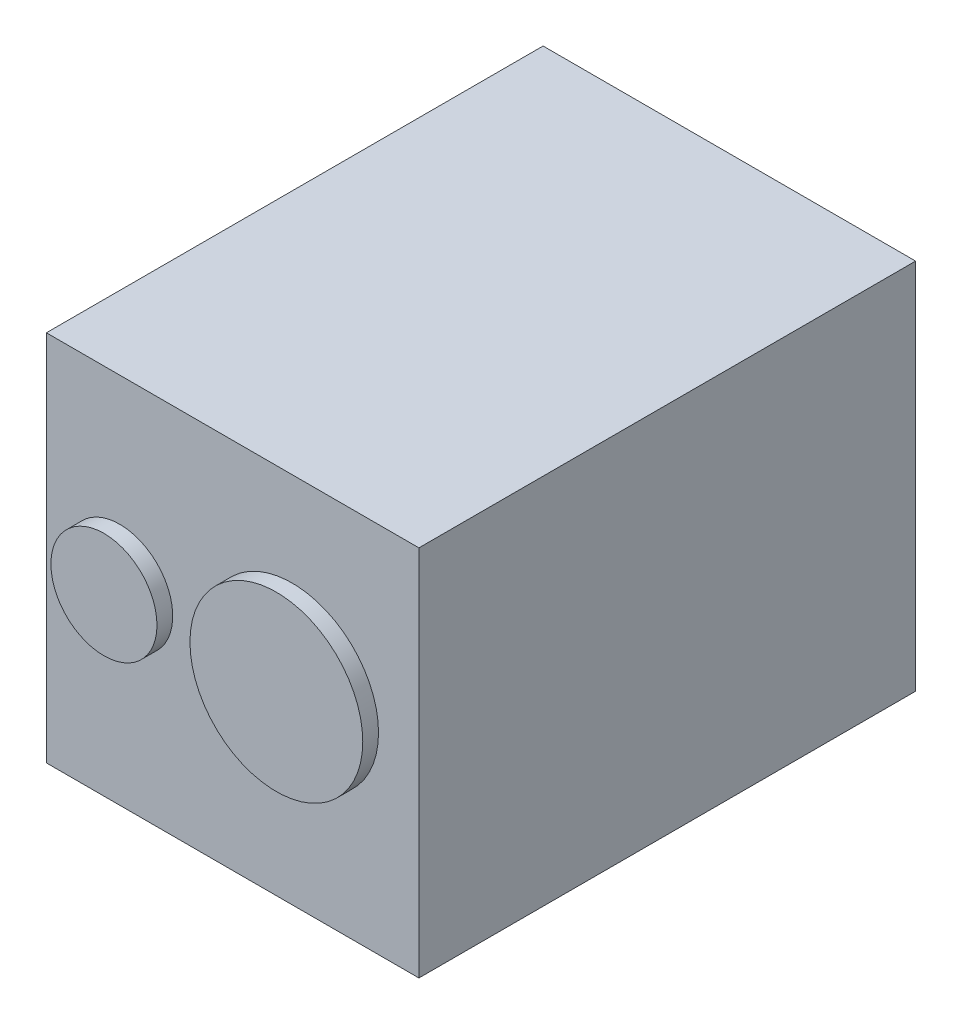
SolidWorks part; units mm, degrees
ref_plane "Front Plane" through (0, 0, 0) normal (0, 0, 1) x (1, 0, 0)
ref_plane "Top Plane" through (0, 0, 0) normal (0, 1, 0) x (1, 0, 0)
ref_plane "Right Plane" through (0, 0, 0) normal (1, 0, 0) x (0, 0, -1)
sketch "Sketch1" plane through (0, 0, 0) normal (0, 0, 1) x (1, 0, 0)
  line L1 (0, 0) -> (300, 0)
  line L2 (0, 0) -> (0, 300)
  line L3 (0, 300) -> (300, 300)
  line L4 (300, 0) -> (300, 300)
extrude "Boss-Extrude1" add sketch "Sketch1" along normal blind 400
sketch "Sketch2" plane through (0, 0, 400) normal (0, 0, 1) x (1, 0, 0)
  circle A0 centre (59.051, 153.2888) radius 42.7046
  circle A1 centre (197.8944, 154.8608) radius 69.588
extrude "Boss-Extrude2" add sketch "Sketch2" along normal blind 12.7
